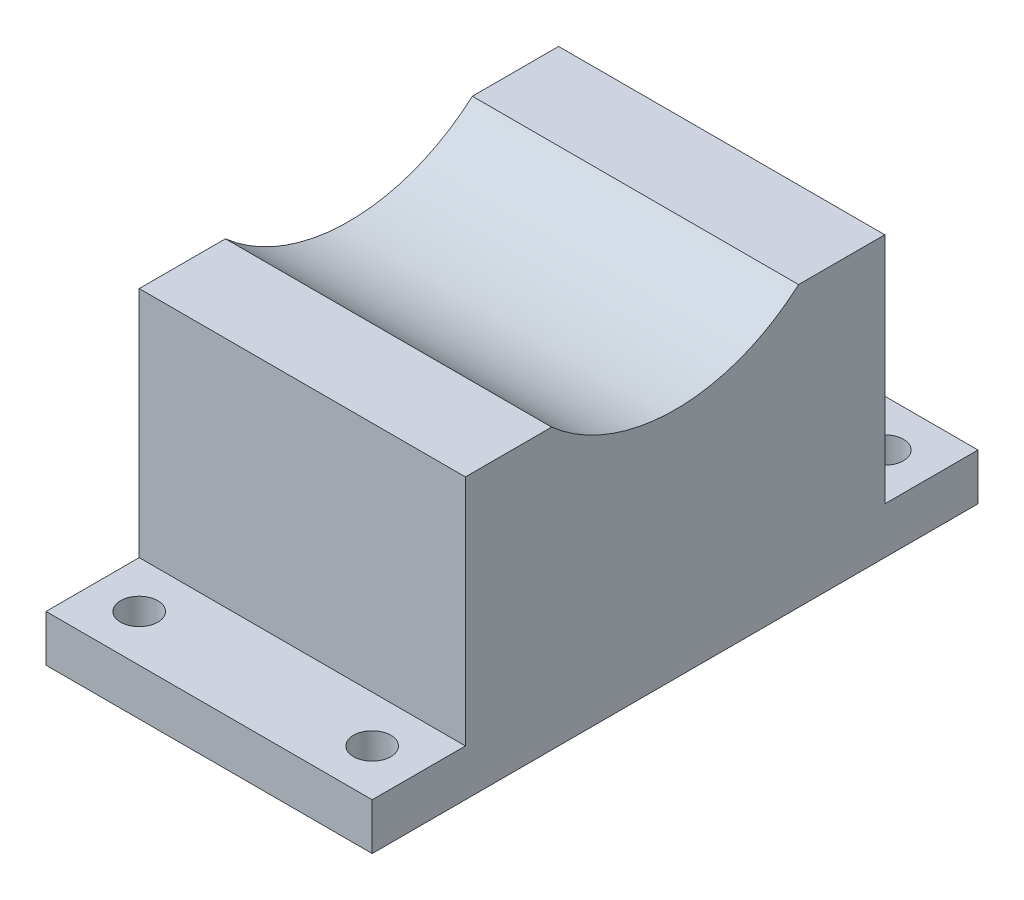
SolidWorks part; units mm, degrees
ref_plane "前视基准面" through (0, 0, 0) normal (0, 0, 1) x (1, 0, 0)
ref_plane "上视基准面" through (0, 0, 0) normal (0, 1, 0) x (1, 0, 0)
ref_plane "右视基准面" through (0, 0, 0) normal (1, 0, 0) x (0, 0, -1)
sketch "草图3" plane through (0, 0, 0) normal (1, 0, 0) x (0, 0, -1)
  line L0 (37.0553, 5.0993) -> (46.308, 5.0993)
  line L1 (-8.692, -24.9007) -> (56.308, -24.9007)
  line L2 (-8.692, -24.9007) -> (-8.692, -19.9007)
  line L3 (1.308, 5.0993) -> (10.5607, 5.0993)
  line L4 (56.308, -24.9007) -> (56.308, -19.9007)
  line L8 (-8.692, -19.9007) -> (1.308, -19.9007)
  line L9 (1.308, 5.0993) -> (1.308, -19.9007)
  line L12 (56.308, -19.9007) -> (46.308, -19.9007)
  line L13 (46.308, 5.0993) -> (46.308, -19.9007)
  arc A0 (10.5607, 5.0993) -> (37.0553, 5.0993) centre (23.808, 20.0993) ccw
  dimension "D1" = 15
  dimension "D2" = 5
  dimension "D3" = 25
  dimension "D4" = 5
  dimension "D5" = 65
  dimension "D6" = 10
  dimension "D7" = 10
  dimension "D8" = 22.5
extrude "凸台-拉伸1" add sketch "草图3" along normal blind 35 contours A0 L0 L13 L12 L4 L1 L2 L8 L9 L3
sketch "草图5" plane through (0, -24.9007, 0) normal (0, -1, 0) x (-1, 0, 0)
  line L0 (-35, -8.692) -> (-35, 56.308) construction
  line L1 (-30, -3.692) -> (-5, -3.692) construction
  line L2 (-30, -3.692) -> (-30, 51.308) construction
  line L3 (-30, 51.308) -> (-5, 51.308) construction
  line L4 (-5, -3.692) -> (-5, 51.308) construction
  line L5 (-30, -3.692) -> (-5, 51.308) construction
  line L6 (-30, 51.308) -> (-5, -3.692) construction
  circle A0 centre (-30, -3.692) radius 2
  circle A1 centre (-5, -3.692) radius 2
  circle A2 centre (-30, 51.308) radius 2
  circle A3 centre (-5, 51.308) radius 2
  point P0 (-17.5, 23.808)
  dimension "D1" = 55
  dimension "D2" = 25
  dimension "D3" = 17.5
extrude "切除-拉伸2" cut sketch "草图5" against normal blind 10
